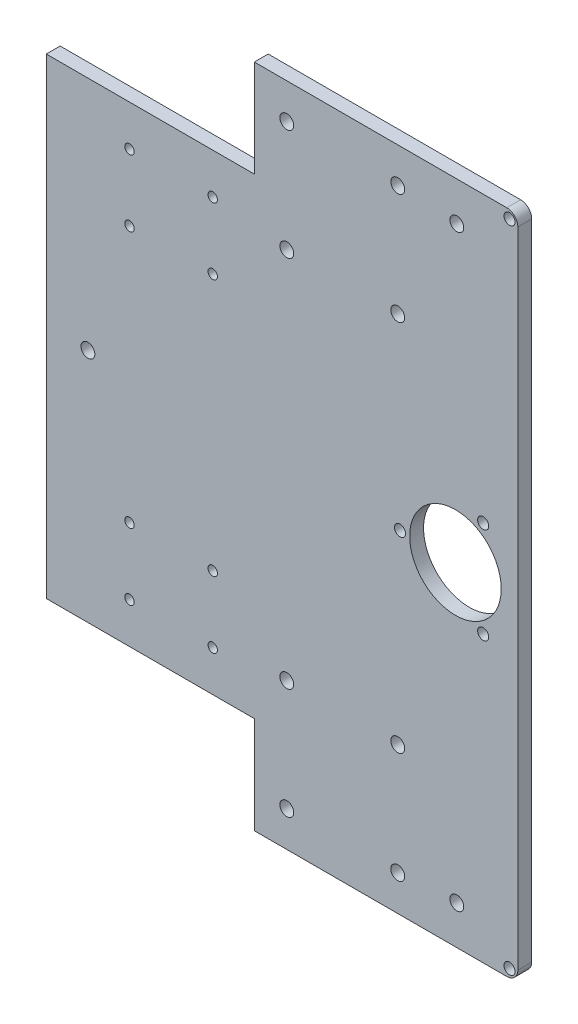
SolidWorks part; units mm, degrees
ref_plane "Front Plane" through (0, 0, 0) normal (0, 0, 1) x (1, 0, 0)
ref_plane "Top Plane" through (0, 0, 0) normal (0, 1, 0) x (1, 0, 0)
ref_plane "Right Plane" through (0, 0, 0) normal (1, 0, 0) x (0, 0, -1)
sketch "Sketch1" plane through (0, 0, 0) normal (0, 0, 1) x (1, 0, 0)
  line L1 (-85, 120) -> (85, 120)
  line L2 (-85, 120) -> (-85, -120)
  line L3 (-85, -120) -> (85, -120)
  line L4 (85, 120) -> (85, -120)
  line L5 (-85, 120) -> (85, -120) construction
  line L6 (-85, -120) -> (85, 120) construction
  point P0 (0, 0)
  dimension "D1" = 240
  dimension "D2" = 170
extrude "Boss-Extrude1" add sketch "Sketch1" along normal blind 5
sketch "Sketch2" plane through (0, 0, 5) normal (0, 0, 1) x (1, 0, 0)
  circle A0 centre (62.5, 0) radius 16.5
  dimension "D1" = 33
extrude "Cut-Extrude1" cut sketch "Sketch2" against normal through all
sketch "Sketch3" plane through (0, 0, 5) normal (0, 0, 1) x (1, 0, 0)
  circle A0 centre (72.5, -17.3205) radius 2
  circle A1 centre (72.5, 17.3205) radius 2
  circle A2 centre (42.5, 0) radius 2
extrude "Cut-Extrude2" cut sketch "Sketch3" against normal through all
sketch "Sketch4" plane through (0, 0, 5) normal (0, 0, 1) x (1, 0, 0)
  line L0 (2.75, 0) -> (-2.75, 0) construction
  circle A0 centre (-25, 46.3125) radius 1.7
  circle A1 centre (-25, 70.3125) radius 1.7
  circle A2 centre (-55, 46.3125) radius 1.7
  circle A3 centre (-55, 70.3125) radius 1.7
  circle A4 centre (-55, -70.3125) radius 1.7
  circle A5 centre (-25, -70.3125) radius 1.7
  circle A6 centre (-55, -46.3125) radius 1.7
  circle A7 centre (-25, -46.3125) radius 1.7
extrude "Cut-Extrude3" cut sketch "Sketch4" against normal through all
sketch "Sketch5" plane through (0, 0, 5) normal (0, 0, 1) x (1, 0, 0)
  line L0 (85, 120) -> (-85, 120) construction
  line L1 (-10, 120) -> (-85, 120)
  line L2 (-10, 120) -> (-10, 85)
  line L3 (-10, 85) -> (-85, 85)
  line L4 (-85, 120) -> (-85, 85)
  line L5 (-85, 120) -> (-85, -120) construction
  line L6 (2.75, 0) -> (-2.75, 0) construction
  line L7 (-10, -120) -> (-85, -120)
  line L8 (-85, -120) -> (-85, -85)
  line L9 (-10, -85) -> (-85, -85)
  line L10 (-10, -120) -> (-10, -85)
  dimension "D1" = 75
  dimension "D2" = 35
extrude "Cut-Extrude4" cut sketch "Sketch5" against normal through all
fillet "Fillet1" radius 4 1 edges at (85, -120, 2.5)
sketch "Sketch6" plane through (0, 0, 5) normal (0, 0, 1) x (1, 0, 0)
  circle A0 centre (82, -117) radius 2
  dimension "D1" = 4
extrude "Cut-Extrude5" cut sketch "Sketch6" against normal through all
mirror "Mirror5" about plane through (0, 0, 0) normal (0, 1, 0) of "Cut-Extrude5"
fillet "Fillet2" radius 4 1 edges at (85, 120, 2.5)
fillet "Fillet3" [suppressed] radius 4
sketch "Sketch7" plane through (0, 0, 5) normal (0, 0, 1) x (1, 0, 0)
  circle A0 centre (41.7, 107.25) radius 2.5
  circle A1 centre (41.7, 67.25) radius 2.5
  circle A2 centre (1.7, 67.25) radius 2.5
  circle A3 centre (1.7, 107.25) radius 2.5
  circle A4 centre (41.7, -107.25) radius 2.5
  circle A5 centre (1.7, -107.25) radius 2.5
  circle A6 centre (1.7, -67.25) radius 2.5
  circle A7 centre (41.7, -67.25) radius 2.5
  dimension "D1" = 5
extrude "Cut-Extrude6" cut sketch "Sketch7" against normal through all
sketch "Sketch8" plane through (0, 0, 0) normal (0, 0, -1) x (-1, 0, 0)
  circle A0 centre (-63, 106) radius 2.5
  circle A1 centre (-63, -106) radius 2.5
  circle A2 centre (70, 0) radius 2.5
  dimension "D1" = 5
extrude "Cut-Extrude7" cut sketch "Sketch8" against normal through all
